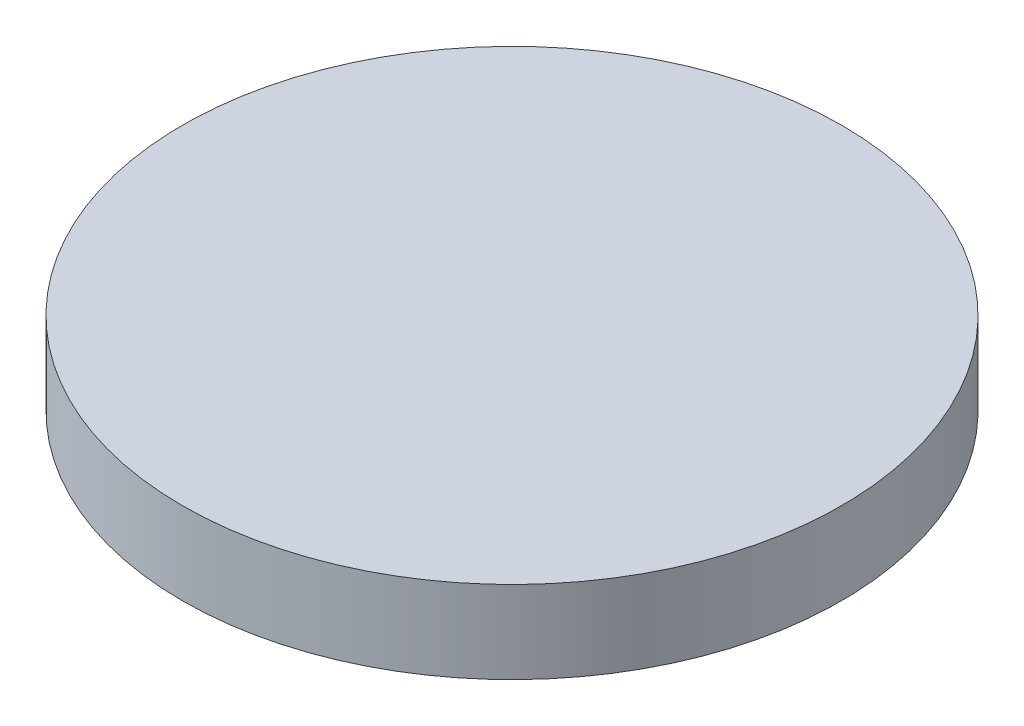
SolidWorks part; units mm, degrees
ref_plane "Front" through (0, 0, 0) normal (0, 0, 1) x (1, 0, 0)
ref_plane "Top" through (0, 0, 0) normal (0, 1, 0) x (1, 0, 0)
ref_plane "Right" through (0, 0, 0) normal (1, 0, 0) x (0, 0, -1)
sketch "Sketch1" plane through (0, 0, 0) normal (0, 1, 0) x (1, 0, 0)
  circle A0 centre (0, 0) radius 4
  dimension "D1" = 8
extrude "Boss-Extrude1" add sketch "Sketch1" along normal blind 1
